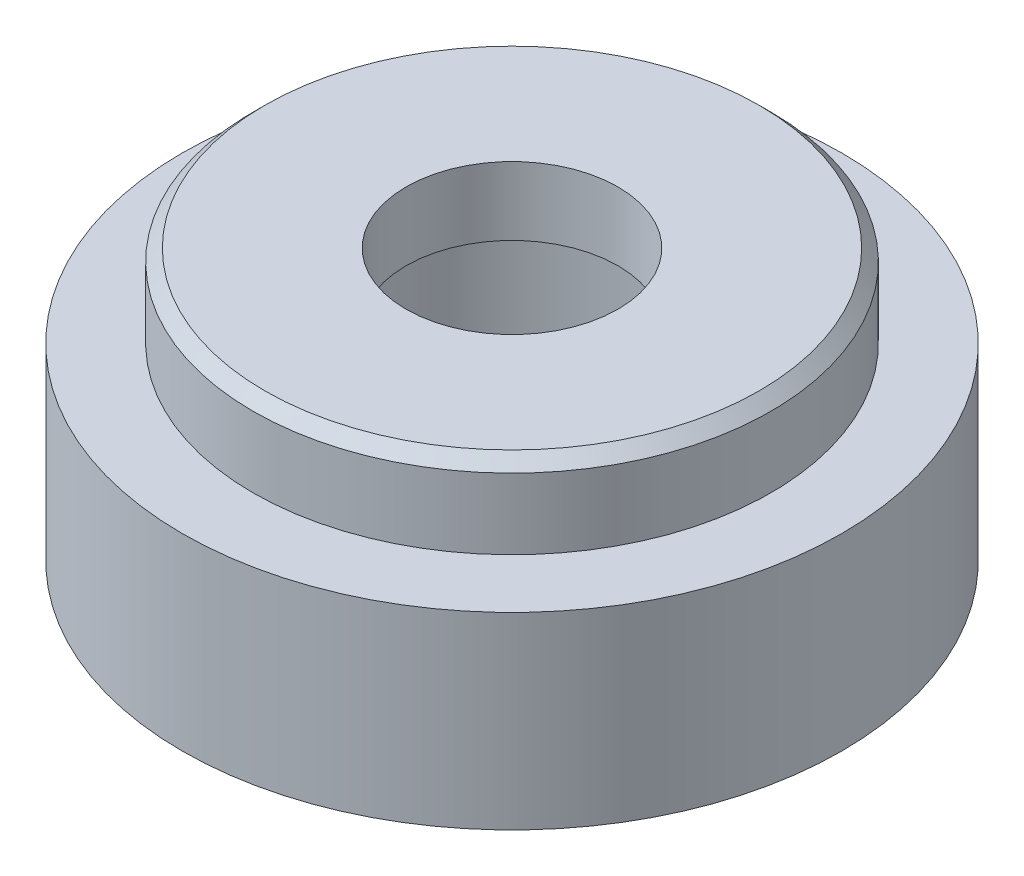
SolidWorks part; units mm, degrees
material "SS41（SS400）"
ref_plane "前基準面" through (0, 0, 0) normal (0, 0, 1) x (1, 0, 0)
ref_plane "上基準面" through (0, 0, 0) normal (0, 1, 0) x (1, 0, 0)
ref_plane "右基準面" through (0, 0, 0) normal (1, 0, 0) x (0, 0, -1)
sketch "草圖1" plane through (0, 0, 0) normal (0, 1, 0) x (1, 0, 0)
  circle A0 centre (0, 0) radius 14
  dimension "D1" = 28
extrude "填料-伸長1" add sketch "草圖1" along normal blind 8
sketch "草圖2" plane through (0, 8, 0) normal (0, 1, 0) x (1, 0, 0)
  circle A0 centre (0, 0) radius 11
  dimension "D1" = 22
extrude "填料-伸長2" add sketch "草圖2" along normal blind 3.5
hole_wizard "M8 六角承窩頭蓋螺釘的柱孔1" positions "草圖3" profile "草圖4" counterbore size "M8" standard "ISO" end condition through all
sketch "草圖3" plane through (0, 0, 0) normal (0, -1, 0) x (-1, 0, 0)
  point P0 (0, 0)
sketch "草圖4" plane through (0, 0, 0) normal (1, 0, 0) x (0, 0, -1)
  line L0 (0, 0) -> (0, 11.5)
  line L1 (0, 11.5) -> (4.5, 11.5)
  line L3 (4.5, 11.5) -> (4.5, 8.6)
  line L4 (4.5, 8.6) -> (7.5, 8.6)
  line L5 (7.5, 8.6) -> (7.5, 0)
  line L7 (7.5, 0) -> (0, 0)
  line L11 (0, -6.35) -> (0, 107.95) construction
  dimension "貫穿孔直徑" = 9
  dimension "貫穿孔深度" = 11.5
  dimension "柱孔直徑" = 15
  dimension "柱孔深度" = 8.6
chamfer "導角1" distance 0.5 angle 45 1 edges at (0, 11.5, 11)
